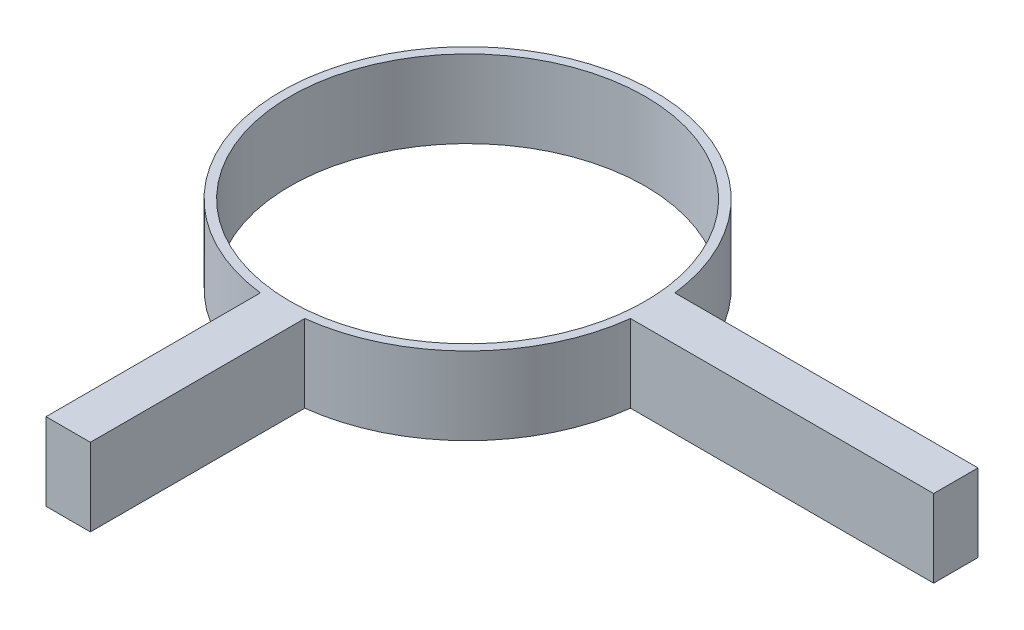
SolidWorks part; units mm, degrees
ref_plane "Front Plane" through (0, 0, 0) normal (0, 0, 1) x (1, 0, 0)
ref_plane "Top Plane" through (0, 0, 0) normal (0, 1, 0) x (1, 0, 0)
ref_plane "Right Plane" through (0, 0, 0) normal (1, 0, 0) x (0, 0, -1)
sketch "Sketch1" plane through (0, 0, 0) normal (0, 1, 0) x (1, 0, 0)
  line L1 (-2, -16.6805) -> (-2, -36)
  line L2 (-2, -36) -> (2, -36)
  line L3 (2, -36) -> (2, -16.6805)
  line L6 (16.6805, 2) -> (44, 2)
  line L7 (44, 2) -> (44, -2)
  line L8 (44, -2) -> (16.6805, -2)
  circle A0 centre (0, 0) radius 16
  circle A1 centre (0, 0) radius 16.8
  point P3 (0, 0)
  point P12 (0, -36)
  point P13 (44, 0)
  point P15 (16.6, 0)
  dimension "D1" = 32
  dimension "D5" = 4
  dimension "D6" = 28
  dimension "D3" = 20
  dimension "D4" = 4
  dimension "D2" = 0.8
extrude "Boss-Extrude1" add sketch "Sketch1" along normal blind 7
